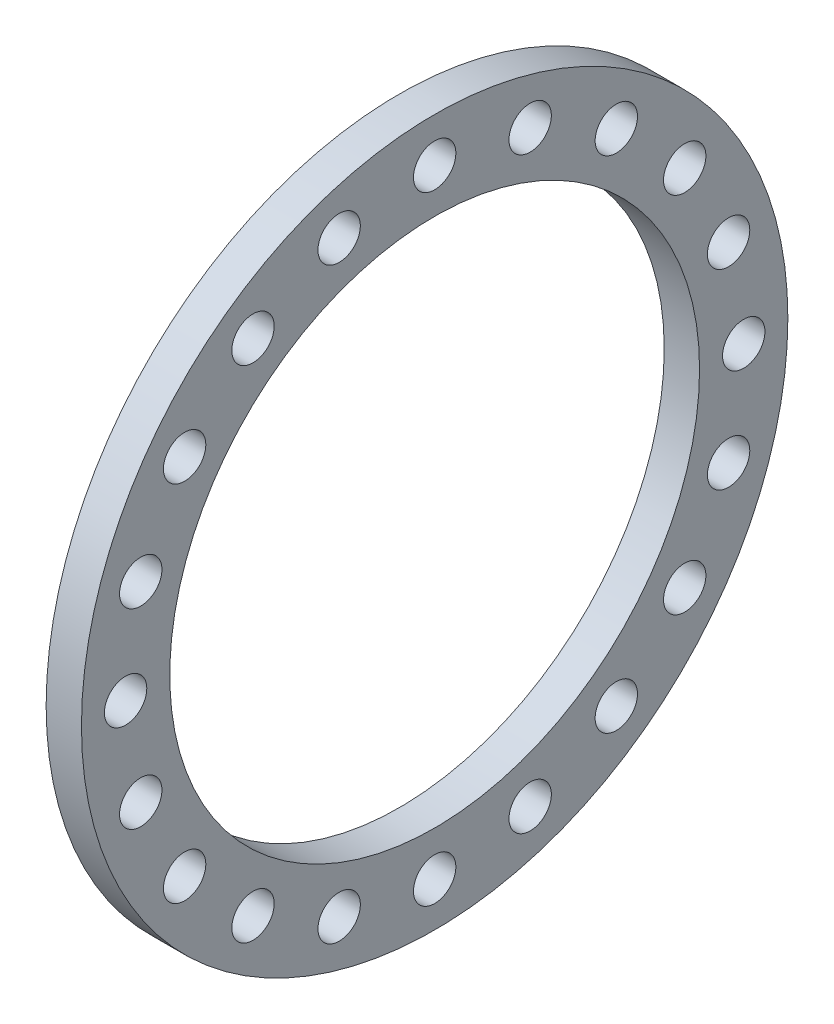
SolidWorks part; units mm, degrees
material "3.3523 (EN-AW 5052)"
ref_plane "Спереди" through (0, 0, 0) normal (0, 0, 1) x (1, 0, 0)
ref_plane "Сверху" through (0, 0, 0) normal (0, 1, 0) x (1, 0, 0)
ref_plane "Справа" through (0, 0, 0) normal (1, 0, 0) x (0, 0, -1)
sketch "Эскиз1" plane through (0, 0, 0) normal (1, 0, 0) x (0, 0, -1)
  line L0 (0, 50) -> (0, 37.5) construction
  circle A0 centre (0, 0) radius 37.5
  circle A1 centre (0, 0) radius 50
  circle A2 centre (0, 43.75) radius 3
  circle A3 centre (13.5195, 41.6087) radius 3
  circle A4 centre (25.7156, 35.3945) radius 3
  circle A5 centre (35.3945, 25.7156) radius 3
  circle A6 centre (41.6087, 13.5195) radius 3
  circle A7 centre (43.75, 0) radius 3
  circle A8 centre (41.6087, -13.5195) radius 3
  circle A9 centre (35.3945, -25.7156) radius 3
  circle A10 centre (25.7156, -35.3945) radius 3
  circle A11 centre (13.5195, -41.6087) radius 3
  circle A12 centre (0, -43.75) radius 3
  circle A13 centre (-13.5195, -41.6087) radius 3
  circle A14 centre (-25.7156, -35.3945) radius 3
  circle A15 centre (-35.3945, -25.7156) radius 3
  circle A16 centre (-41.6087, -13.5195) radius 3
  circle A17 centre (-43.75, 0) radius 3
  circle A18 centre (-41.6087, 13.5195) radius 3
  circle A19 centre (-35.3945, 25.7156) radius 3
  circle A20 centre (-25.7156, 35.3945) radius 3
  circle A21 centre (-13.5195, 41.6087) radius 3
  point P48 (0, 0)
  dimension "D1" = 75
  dimension "D2" = 100
  dimension "D3" = 20
extrude "Бобышка-Вытянуть1" add sketch "Эскиз1" along normal blind 5
